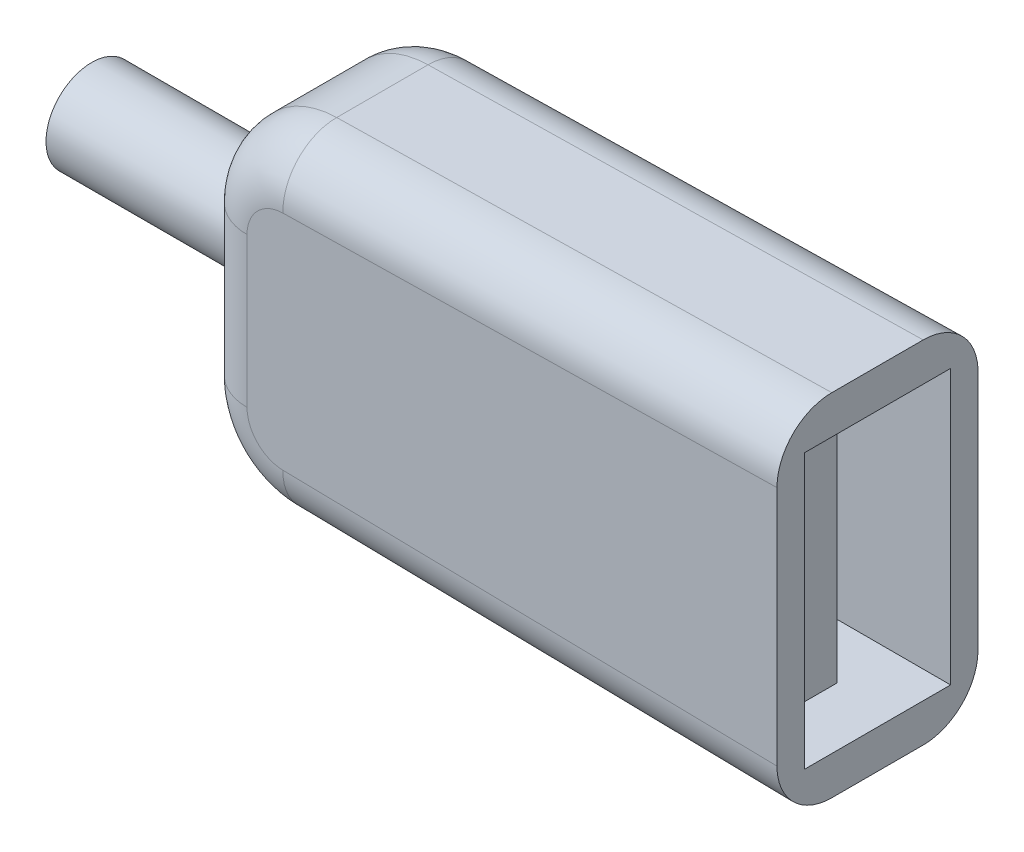
SolidWorks part; units mm, degrees
ref_plane "Alzado" through (0, 0, 0) normal (0, 0, 1) x (1, 0, 0)
ref_plane "Planta" through (0, 0, 0) normal (0, 1, 0) x (1, 0, 0)
ref_plane "Vista lateral" through (0, 0, 0) normal (1, 0, 0) x (0, 0, -1)
sketch "Croquis1" plane through (0, 0, 0) normal (0, 0, 1) x (1, 0, 0)
  line L0 (0, 9.6) -> (0, -9.6)
  line L1 (0, -9.6) -> (-32, -9)
  line L2 (-32, -9) -> (-32, 9)
  line L3 (-32, 9) -> (0, 9.6)
  line L4 (-32, 0) -> (0, 0) construction
  point P4 (0, 0)
  dimension "D1" = 18
  dimension "D2" = 19.2
  dimension "D3" = 32
extrude "Saliente-Extruir1" add sketch "Croquis1" along normal blind 11
fillet "Redondeo1" radius 5 2 edges at (-32, -9, 5.5) (-32, 9, 5.5)
fillet "Redondeo2" radius 3 10 edges at (-13.5469, -9.346, 0) (-30.5685, -7.5951, 0) (-32, 0, 0) (-30.5685, 7.5951, 0) (-13.5469, 9.346, 11) (-30.5685, 7.5951, 11) (-32, 0, 11) (-30.5685, -7.5951, 11) (-13.5469, 9.346, 0) (-13.5469, -9.346, 11)
sketch "Croquis2" plane through (-32, 0, 0) normal (-1, 0, 0) x (0, 0, 1)
  line L0 (8, 4.0929) -> (3, -4.0929) construction
  circle A0 centre (5.5, 0) radius 2.5
  dimension "D1" = 5
extrude "Saliente-Extruir2" add sketch "Croquis2" along normal blind 11
sketch "Croquis3" plane through (0, 0, 0) normal (1, 0, 0) x (0, 0, -1)
  line L0 (-5.5, 9.6) -> (-5.5, -9.6) construction
  line L1 (-8, 9.6) -> (-3, 9.6) construction
  line L2 (-8, -9.6) -> (-3, -9.6) construction
  line L4 (-9.5, -7.5) -> (-1.5, -7.5)
  line L5 (-9.5, -7.5) -> (-9.5, 7.5)
  line L6 (-9.5, 7.5) -> (-1.5, 7.5)
  line L7 (-1.5, -7.5) -> (-1.5, 7.5)
  line L8 (-9.5, -7.5) -> (-1.5, 7.5) construction
  line L9 (-9.5, 7.5) -> (-1.5, -7.5) construction
  point P6 (-5.5, 0)
  dimension "D1" = 8
  dimension "D2" = 15
extrude "Cortar-Extruir1" cut sketch "Croquis3" against normal blind 15
sketch "Croquis4" plane through (-15, 0, 0) normal (1, 0, 0) x (0, 0, -1)
  line L1 (-7.562, 6.2959) -> (-5.7044, 6.2959)
  line L2 (-7.562, 6.2959) -> (-7.562, -6.3006)
  line L3 (-7.562, -6.3006) -> (-5.7044, -6.3006)
  line L4 (-5.7044, 6.2959) -> (-5.7044, -6.3006)
  point P4 (-5.7044, 6.2959)
extrude "Saliente-Extruir3" add sketch "Croquis4" along normal blind 13
